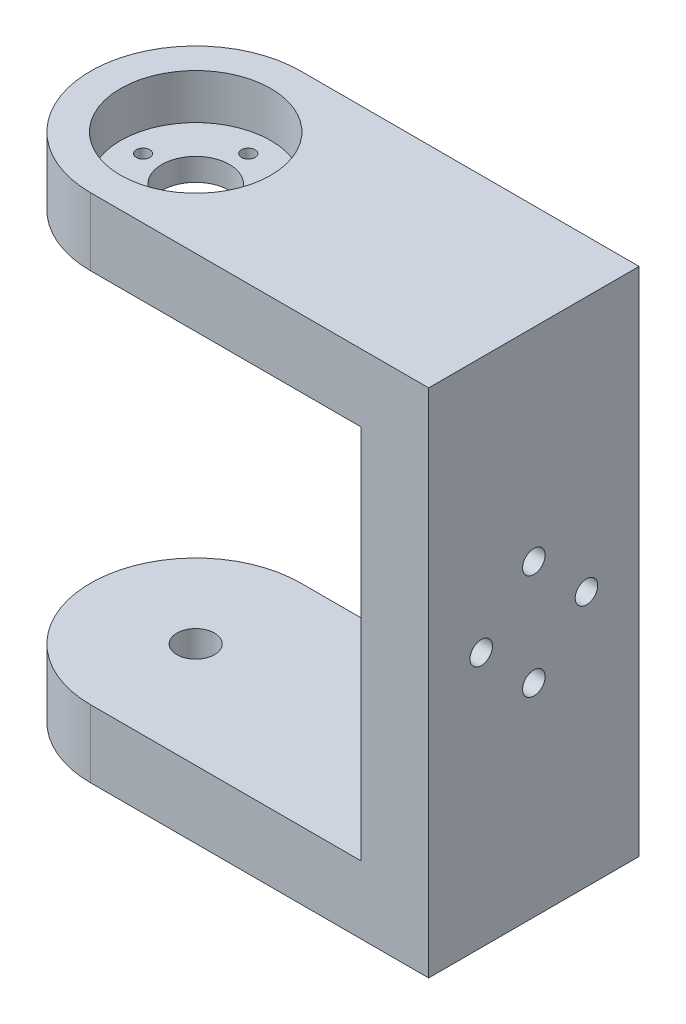
SolidWorks part; units mm, degrees
ref_plane "Front Plane" through (0, 0, 0) normal (0, 0, 1) x (1, 0, 0)
ref_plane "Top Plane" through (0, 0, 0) normal (0, 1, 0) x (1, 0, 0)
ref_plane "Right Plane" through (0, 0, 0) normal (1, 0, 0) x (0, 0, -1)
sketch "Sketch1" plane through (0, 0, 0) normal (0, 0, 1) x (1, 0, 0)
  line L1 (-7.8793, 35.8017) -> (1.1207, 35.8017)
  line L2 (-7.8793, 35.8017) -> (-7.8793, -32.1983)
  line L3 (-7.8793, -32.1983) -> (1.1207, -32.1983)
  line L4 (1.1207, 35.8017) -> (1.1207, -32.1983)
  line L5 (-7.8793, 35.8017) -> (-57.8793, 35.8017)
  line L6 (-7.8793, 35.8017) -> (-7.8793, 26.8017)
  line L7 (-7.8793, 26.8017) -> (-57.8793, 26.8017)
  line L8 (-57.8793, 35.8017) -> (-57.8793, 26.8017)
  line L9 (-7.8793, -32.1983) -> (-57.8793, -32.1983)
  line L10 (-7.8793, -32.1983) -> (-7.8793, -23.1983)
  line L11 (-7.8793, -23.1983) -> (-57.8793, -23.1983)
  line L12 (-57.8793, -32.1983) -> (-57.8793, -23.1983)
  dimension "D1" = 9
  dimension "D2" = 68
  dimension "D3" = 9
  dimension "D4" = 9
  dimension "D5" = 50
  dimension "D6" = 50
extrude "Boss-Extrude1" add sketch "Sketch1" along normal blind 28 contours L5 L8 L7 L2 | L4 L1 L2 L3 | L12 L9 L2 L11
sketch "Sketch2" plane through (0, 35.8017, 0) normal (0, 1, 0) x (1, 0, 0)
  line L0 (-57.8793, -14) -> (-57.8793, 0)
  line L1 (-57.8793, 0) -> (-43.8793, 0)
  line L2 (-43.8793, -28) -> (-57.8793, -28)
  line L3 (-57.8793, -28) -> (-57.8793, -14)
  circle A0 centre (-43.8793, -14) radius 10
  circle A1 centre (-43.8793, -14) radius 2.5
  circle A2 centre (-43.8793, -14) radius 4.5
  circle A3 centre (-43.8793, -14) radius 14
  line M4 (1.1207, 0) -> (-57.8793, 0)
  line M5 (-57.8793, 0) -> (-57.8793, -28)
  line M6 (-57.8793, -28) -> (1.1207, -28)
  dimension "D1" = 20
  dimension "D5" = 5
  dimension "D6" = 9
  dimension "D2" = 14
  dimension "D3" = 14
  dimension "D4" = 14
extrude "Cut-Extrude2" cut sketch "Sketch2" against normal blind 100 contours A1 | A3 M5 M6 | A3 M4 M5
sketch "Sketch4" plane through (0, 35.8017, 0) normal (0, 1, 0) x (1, 0, 0)
  circle A0 centre (-43.8793, -14) radius 4.5
  dimension "D1" = 9
extrude "Cut-Extrude3" cut sketch "Sketch4" against normal blind 10
sketch "Sketch5" plane through (0, 35.8017, 0) normal (0, 1, 0) x (1, 0, 0)
  circle A0 centre (-43.8793, -14) radius 10
extrude "Cut-Extrude4" cut sketch "Sketch5" against normal blind 6
sketch "Sketch6" plane through (0, -32.1983, 0) normal (0, -1, 0) x (1, 0, 0)
  line L0 (1.1207, 28) -> (1.1207, 0) construction
  circle A0 centre (-43.8793, 14) radius 5.6237
  dimension "D1" = 45
sketch "Sketch7" plane through (1.1207, 0, 0) normal (1, 0, 0) x (0, 0, -1)
  circle A0 centre (-14, 8.8017) radius 1.5
  circle A1 centre (-14, -5.1983) radius 1.5
  circle A2 centre (-7, 1.8017) radius 1.5
  circle A3 centre (-21, 1.8017) radius 1.5
  point P10 (0, 0)
  point P11 (0, 0)
  dimension "D1" = 3
  dimension "D2" = 3
  dimension "D6" = 3
  dimension "D7" = 3
  dimension "D3" = 14
  dimension "D4" = 14
  dimension "D5" = 14
  dimension "D8" = 14
  dimension "D9" = 7
  dimension "D10" = 7
  dimension "D11" = 27
  dimension "D12" = 27
  dimension "D13" = 7
extrude "Cut-Extrude5" cut sketch "Sketch7" against normal blind 10
sketch "Sketch8" plane through (0, 29.8017, 0) normal (0, 1, 0) x (1, 0, 0)
  line L0 (-43.8793, -14) -> (-57.8793, -14)
  line L1 (-57.8793, -14) -> (1.1207, -14)
  line L2 (1.1207, -28) -> (1.1207, 0) construction
  line L3 (-43.8793, -14) -> (-43.8793, -28)
  line L4 (-43.8793, -28) -> (-43.8793, 0)
  circle A0 centre (-43.8793, -7) radius 0.9
  circle A1 centre (-36.8793, -14) radius 0.9
  circle A2 centre (-50.8793, -14) radius 0.9
  circle A3 centre (-43.8793, -21.003) radius 0.9
  arc A4 (-43.8793, 0) -> (-43.8793, -28) centre (-43.8793, -14) ccw construction
  dimension "D1" = 1.8
  dimension "D2" = 1.8
  dimension "D3" = 1.8
  dimension "D4" = 1.8
  dimension "D5" = 7
  dimension "D6" = 7.003
  dimension "D7" = 7
  dimension "D8" = 7
  dimension "D9" = 0
  dimension "D10" = 0
  dimension "D11" = 0
  dimension "D12" = 0
extrude "Cut-Extrude6" cut sketch "Sketch8" against normal blind 10 contours L4 A3 | L4 A3 | L1 A1 | L1 A1 | L4 A0 | L4 A0 | L1 A2 | L1 A2
